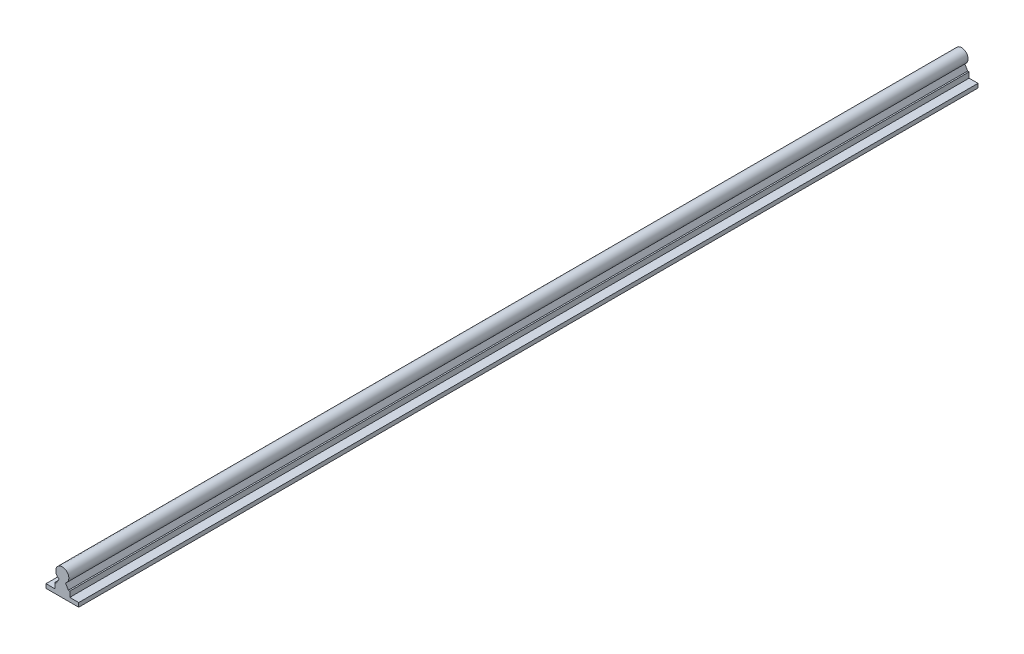
SolidWorks part; units mm, degrees
ref_plane "Plan de face" through (0, 0, 0) normal (0, 0, 1) x (1, 0, 0)
ref_plane "Plan de dessus" through (0, 0, 0) normal (0, 1, 0) x (1, 0, 0)
ref_plane "Plan de droite" through (0, 0, 0) normal (1, 0, 0) x (0, 0, -1)
sketch "Esquisse1" plane through (0, 0, 0) normal (0, 0, 1) x (1, 0, 0)
  line L0 (-25.9313, -2.761) -> (-15.1813, -2.761)
  line L1 (-15.1813, -2.761) -> (-15.1813, 3.939)
  line L2 (-15.1813, 3.939) -> (-13.4531, 3.939)
  line L3 (-13.4531, 3.939) -> (-9.9313, 10.039)
  line L5 (-2.0896, 10.039) -> (1.4322, 3.939)
  line L6 (1.4322, 3.939) -> (3.1604, 3.939)
  line L7 (3.1604, 3.939) -> (3.1604, -2.761)
  line L8 (3.1604, -2.761) -> (14.0687, -2.761)
  line L9 (14.0687, -2.761) -> (14.0687, -7.761)
  line L14 (14.0687, -7.761) -> (-25.9313, -7.761)
  line L15 (-25.9313, -7.761) -> (-25.9313, -2.761)
  line L16 (-25.9313, -2.761) -> (-25.9155, -2.8404)
  arc A1 (-9.9313, 10.039) -> (-2.0896, 10.039) centre (-6.0104, 17.0123) cw
  dimension "D1" = 8
extrude "Boss.-Extru.1" add sketch "Esquisse1" along normal blind 1100 contours L0 L1 L2 L3 A1 L5 L6 L7 L8 L9 L14 L15
